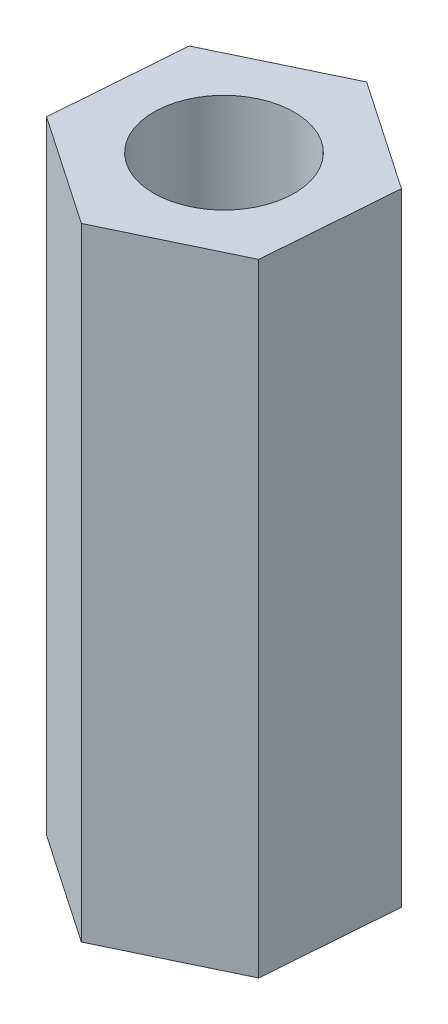
SolidWorks part; units mm, degrees
material "1060 Alloy"
ref_plane "Front Plane" through (0, 0, 0) normal (0, 0, 1) x (1, 0, 0)
ref_plane "Top Plane" through (0, 0, 0) normal (0, 1, 0) x (1, 0, 0)
ref_plane "Right Plane" through (0, 0, 0) normal (1, 0, 0) x (0, 0, -1)
sketch "Sketch1" plane through (0, 0, 0) normal (0, 1, 0) x (1, 0, 0)
  line L1 (2.4462, 1.1745) -> (0.2059, 2.7057)
  line L2 (0.2059, 2.7057) -> (-2.2402, 1.5312)
  line L3 (-2.2402, 1.5312) -> (-2.4462, -1.1745)
  line L4 (-2.4462, -1.1745) -> (-0.2059, -2.7057)
  line L5 (-0.2059, -2.7057) -> (2.2402, -1.5312)
  line L6 (2.2402, -1.5312) -> (2.4462, 1.1745)
  circle A0 centre (0, 0) radius 2.35 construction
  dimension "D1" = 4.7
extrude "Boss-Extrude1" add sketch "Sketch1" along normal blind 12.7
sketch "Sketch2" plane through (0, 12.7, 0) normal (0, 1, 0) x (1, 0, 0)
  circle A0 centre (0, 0) radius 1.435
  dimension "D1" = 2.87
extrude "Cut-Extrude1" cut sketch "Sketch2" against normal through all
